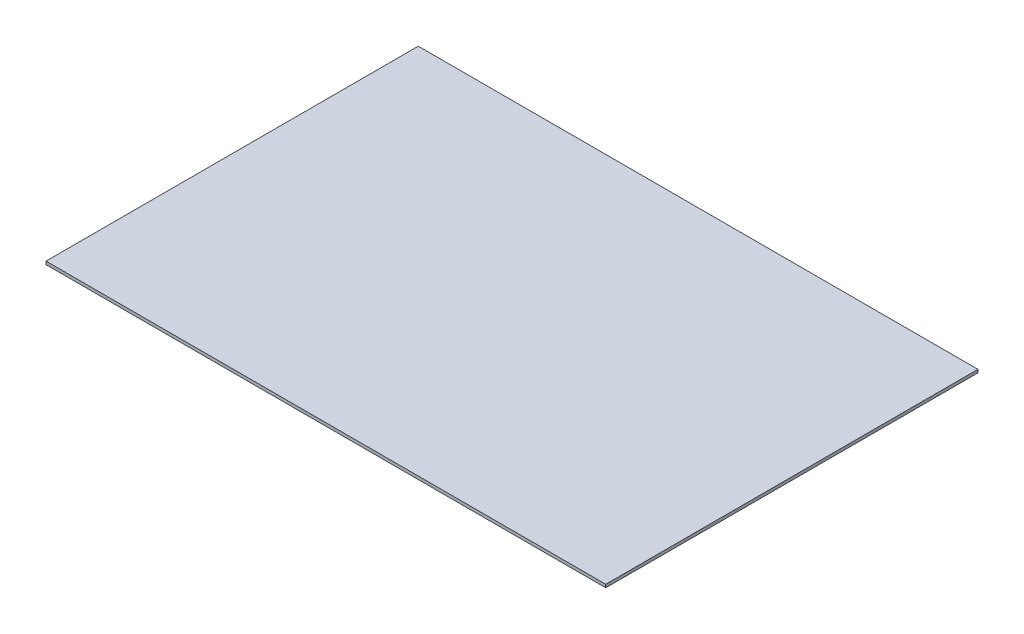
SolidWorks part; units mm, degrees
material "Glass"
ref_plane "Front Plane" through (0, 0, 0) normal (0, 0, 1) x (1, 0, 0)
ref_plane "Top Plane" through (0, 0, 0) normal (0, 1, 0) x (1, 0, 0)
ref_plane "Right Plane" through (0, 0, 0) normal (1, 0, 0) x (0, 0, -1)
sketch "Sketch1" plane through (0, 0, 0) normal (0, 1, 0) x (1, 0, 0)
  line L1 (-127.5983, 73.7962) -> (146.5017, 73.7962)
  line L2 (-127.5983, 73.7962) -> (-127.5983, -108.5038)
  line L3 (-127.5983, -108.5038) -> (146.5017, -108.5038)
  line L4 (146.5017, 73.7962) -> (146.5017, -108.5038)
  dimension "D1" = 274.1
  dimension "D2" = 182.3
extrude "Boss-Extrude1" add sketch "Sketch1" along normal blind 1.5
